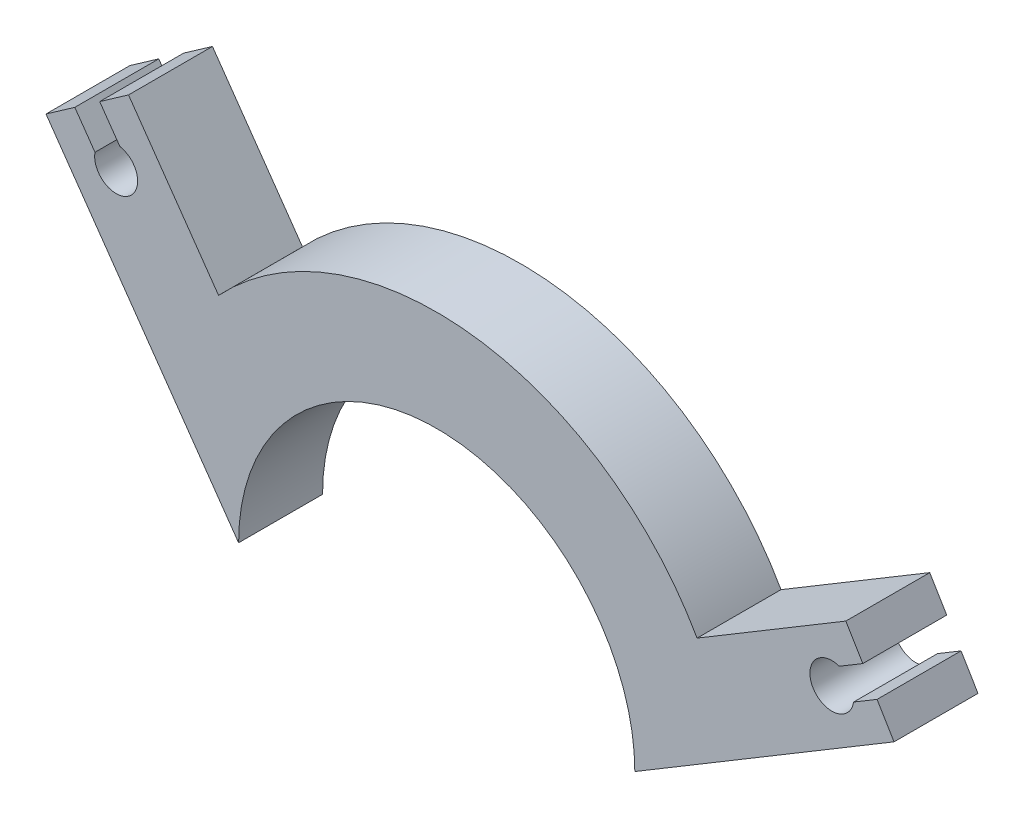
SolidWorks part; units mm, degrees
ref_plane "Front Plane" through (0, 0, 0) normal (0, 0, 1) x (1, 0, 0)
ref_plane "Top Plane" through (0, 0, 0) normal (0, 1, 0) x (1, 0, 0)
ref_plane "Right Plane" through (0, 0, 0) normal (1, 0, 0) x (0, 0, -1)
sketch "Sketch2" plane through (0, 0, 0) normal (0, 0, 1) x (1, 0, 0)
  line L0 (-3.7465, 0) -> (-7.3887, 5.2016)
  line L1 (3.7465, 0) -> (8.6488, 2.9375)
  line L2 (8.6488, 2.9375) -> (8.3278, 3.4731)
  line L3 (7.7367, 4.4597) -> (4.9238, 2.7741)
  line L4 (-7.3887, 5.2016) -> (-6.8439, 5.5831)
  line L5 (-5.8282, 6.2943) -> (-4.1255, 3.8626)
  line L6 (-6.742, 5.9386) -> (-3.66, 1.5372) construction
  line L7 (-6.8439, 5.5831) -> (-6.4624, 5.0383)
  line L8 (-6.3731, 5.9128) -> (-5.9916, 5.3679)
  line L9 (-6.3731, 5.9128) -> (-5.8282, 6.2943)
  line L10 (8.1927, 3.6986) -> (7.4726, 3.2671) construction
  line L11 (8.3278, 3.4731) -> (7.883, 3.2065)
  line L12 (8.0576, 3.9241) -> (7.6127, 3.6575)
  line L13 (8.0576, 3.9241) -> (7.7367, 4.4597)
  arc A0 (3.7465, 0) -> (-3.7465, 0) centre (0, 0) ccw
  arc A1 (4.9238, 2.7741) -> (-4.1255, 3.8626) centre (0, 0) ccw
  circle A2 centre (0, 0) radius 5.6515 construction
  circle A3 centre (0, 0) radius 3.7465 construction
  arc A4 (-6.4624, 5.0383) -> (-5.9916, 5.3679) centre (-6.0621, 4.9677) ccw
  arc A5 (7.6127, 3.6575) -> (7.883, 3.2065) centre (7.4726, 3.2671) ccw
  dimension "D1" = 7.493
  dimension "D5" = 0.8128
  dimension "D3" = 6.35
  dimension "D4" = 5.715
  dimension "D6" = 1.905
  dimension "D7" = 0.8395
  dimension "D8" = 0.8872
  dimension "D9" = 0.8872
  dimension "D2" = 1.905
extrude "Boss-Extrude1" add sketch "Sketch2" along normal blind 1.5875
equation "\"D8@Sketch2\" = \"D9@Sketch2\""
